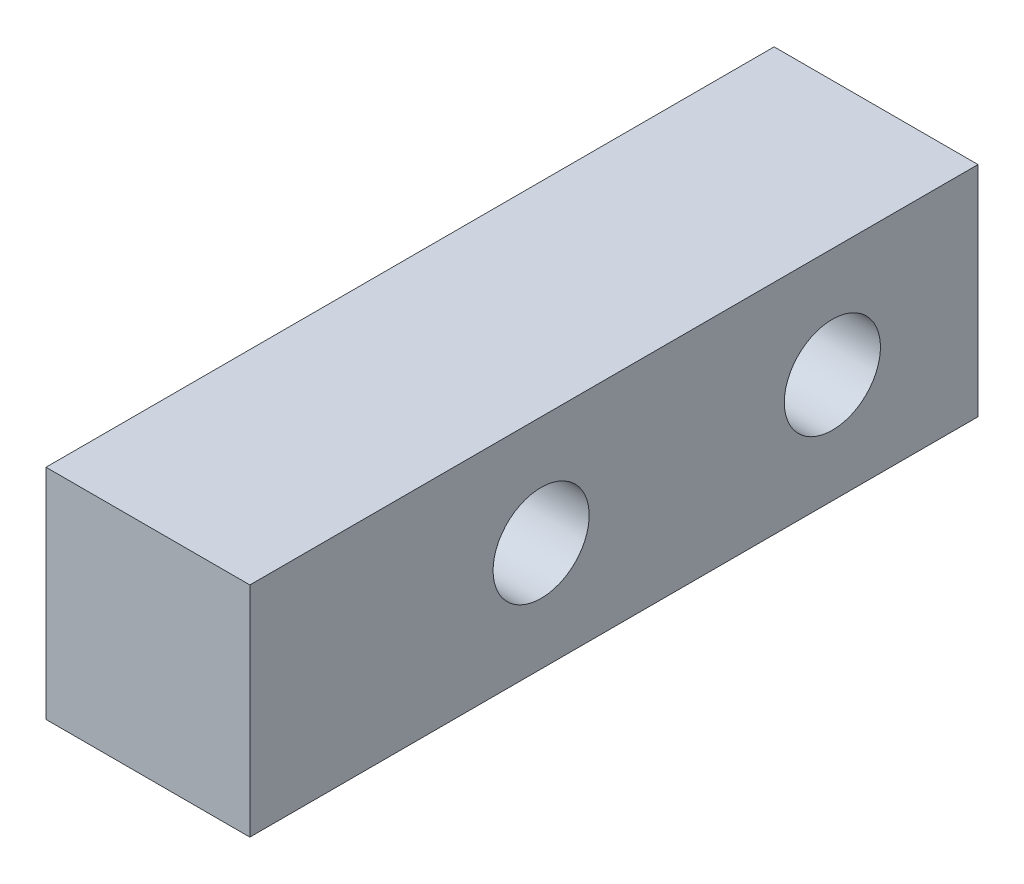
SolidWorks part; units mm, degrees
material "Natural Rubber"
ref_plane "Front Plane" through (0, 0, 0) normal (0, 0, 1) x (1, 0, 0)
ref_plane "Top Plane" through (0, 0, 0) normal (0, 1, 0) x (1, 0, 0)
ref_plane "Right Plane" through (0, 0, 0) normal (1, 0, 0) x (0, 0, -1)
sketch "Sketch1" plane through (0, 0, 0) normal (0, 0, 1) x (1, 0, 0)
  line L5 (7, 7.5) -> (-7, 7.5)
  line L6 (7, 7.5) -> (7, -7.5)
  line L7 (7, -7.5) -> (-7, -7.5)
  line L8 (-7, 7.5) -> (-7, -7.5)
  line L9 (7, 7.5) -> (-7, -7.5) construction
  line L10 (7, -7.5) -> (-7, 7.5) construction
  point P0 (0, 0)
  dimension "D1" = 14
  dimension "15" = 15
extrude "Boss-Extrude1" add sketch "Sketch1" along normal blind 50
hole_wizard "CBORE for M6 Hex Head Bolt1" positions "Sketch2" profile "Sketch3" counterbore size "M6" standard "ISO" end condition through all
sketch "Sketch2" plane through (-7, 0, 0) normal (-1, 0, 0) x (0, 0, 1)
  point P0 (10, 0)
  point P2 (30, 0)
  dimension "D1" = 10
  dimension "D2" = 30
sketch "Sketch3" plane through (-7, 0, 10) normal (0, 1, 0) x (0, 0, 1)
  line L0 (0, 0) -> (0, 14)
  line L1 (0, 14) -> (3.3, 14)
  line L3 (3.3, 14) -> (3.3, 8)
  line L4 (7.2735, 8) -> (3.3, 8)
  line L5 (7.2735, 8) -> (7.2735, 0.025)
  line L6 (7.2735, 0.025) -> (7.2985, 0)
  line L7 (7.2985, 0) -> (0, 0)
  line L8 (-7.2735, 0.025) -> (-7.2985, 0) construction
  line L11 (0, -6.35) -> (0, 107.95) construction
  dimension "Thru Hole Dia." = 6.6
  dimension "Thru Hole Depth" = 14
  dimension "C'Bore Dia." = 14.547
  dimension "C'Bore Depth" = 8
  dimension "Near C'Sink Dia." = 14.597
  dimension "Near C'Sink Angle" = 90
